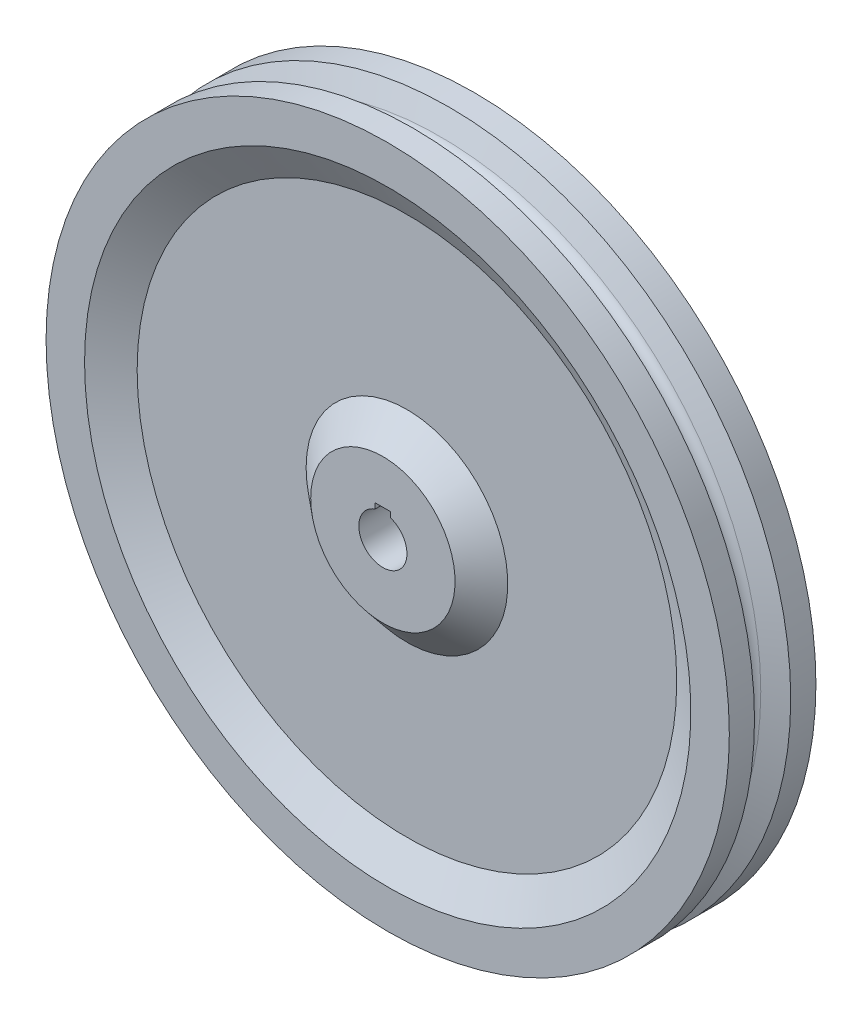
SolidWorks part; units mm, degrees
ref_plane "Plan de face" through (0, 0, 0) normal (0, 0, 1) x (1, 0, 0)
ref_plane "Plan de dessus" through (0, 0, 0) normal (0, 1, 0) x (1, 0, 0)
ref_plane "Plan de droite" through (0, 0, 0) normal (1, 0, 0) x (0, 0, -1)
sketch "Esquisse1" plane through (0, 0, 0) normal (1, 0, 0) x (0, 0, -1)
  line L0 (0, 0) -> (-50, 0)
  line L1 (-50, 0) -> (-50, 75)
  line L2 (-50, 75) -> (-25, 104.7938)
  line L3 (-25, 104.7938) -> (-25, 280.359)
  line L4 (-25, 280.359) -> (-45, 315)
  line L5 (-45, 315) -> (-45, 355)
  line L6 (-45, 355) -> (-18.821, 355)
  line L7 (-18.821, 355) -> (-9.7007, 332.9818)
  line L8 (0, 326.5) -> (0, 0)
  line L10 (0, 326.5) -> (32.0144, 326.5) construction
  arc A1 (-9.7007, 332.9818) -> (0, 326.5) centre (0, 337) ccw
  dimension "D5" = 10.5
  dimension "D1" = 50
  dimension "D2" = 25
  dimension "D3" = 45
  dimension "D4" = 28.5
  dimension "D6" = 67.5
  dimension "D7" = 40
  dimension "D8" = 30
  dimension "D9" = 75
  dimension "D10" = 355
  dimension "D11" = 40
revolve "Révolution1" add sketch "Esquisse1" angle 360 about L0
mirror "Symétrie1" about plane through (0, 326.5, 0) normal (0, 0, -1) of "Révolution1"
sketch "Esquisse2" plane through (0, 0, 50) normal (0, 0, 1) x (1, 0, 0)
  circle A0 centre (0, 0) radius 25
  dimension "D1" = 50
extrude "Enlèv. mat.-Extru.1" cut sketch "Esquisse2" against normal through all
sketch "Esquisse3" plane through (0, 0, 50) normal (0, 0, 1) x (1, 0, 0)
  line L0 (0, 0) -> (0, 25) construction
  line L2 (8, 20.7) -> (-8, 20.7)
  line L3 (8, 20.7) -> (8, 29.3)
  line L4 (8, 29.3) -> (-8, 29.3)
  line L5 (-8, 20.7) -> (-8, 29.3)
  line L6 (8, 20.7) -> (-8, 29.3) construction
  line L7 (8, 29.3) -> (-8, 20.7) construction
  circle A0 centre (0, 0) radius 25 construction
  dimension "D1" = 16
  dimension "D2" = 8.6
extrude "Enlèv. mat.-Extru.2" cut sketch "Esquisse3" against normal through all
